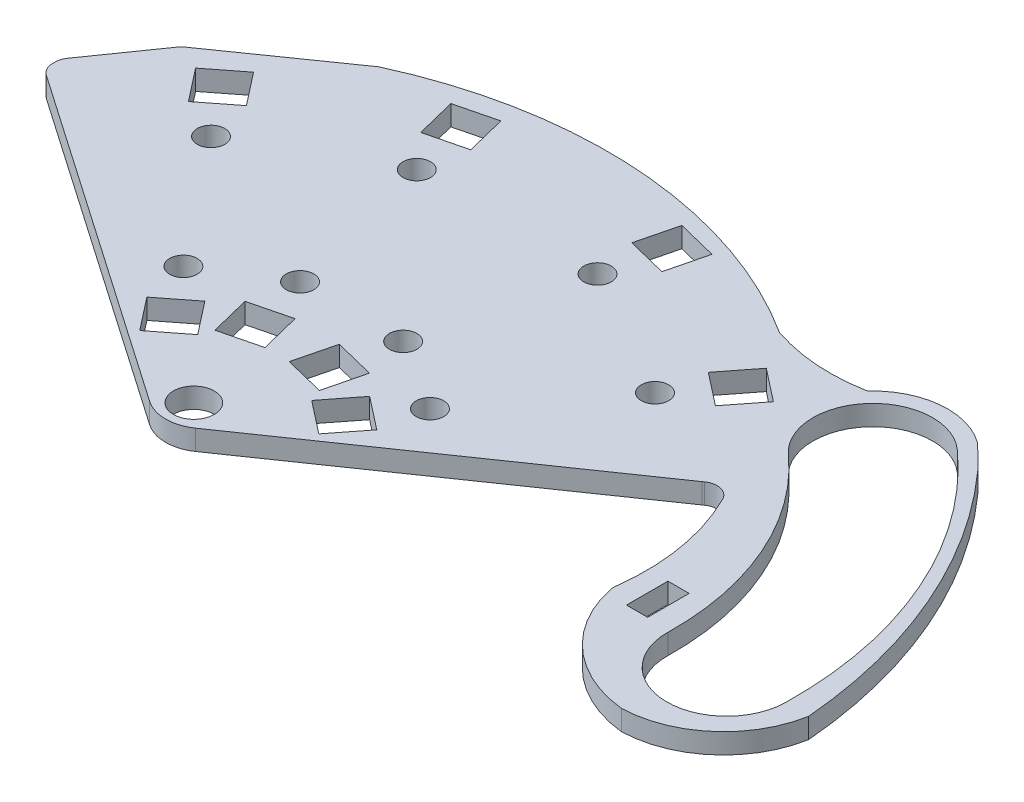
SolidWorks part; units mm, degrees
ref_plane "Front Plane" through (0, 0, 0) normal (0, 0, 1) x (1, 0, 0)
ref_plane "Top Plane" through (0, 0, 0) normal (0, 1, 0) x (1, 0, 0)
ref_plane "Right Plane" through (0, 0, 0) normal (1, 0, 0) x (0, 0, -1)
sketch "Sketch1" plane through (0, 0, 0) normal (0, 1, 0) x (1, 0, 0)
  line L0 (0, 0) -> (0, 16.5491) construction
  line L1 (46.4032, 26.2532) -> (50.582, 29.1399)
  line L2 (-57.15, 35.4293) -> (-57.15, 35.0096)
  line L3 (-48.9805, 47.6303) -> (-31.1233, 60.1341)
  line L4 (-46.4032, 26.2532) -> (-50.582, 29.1399)
  line L5 (-14.1946, 62.3609) -> (-20.4792, 60.794)
  line L6 (-3.4719, 19.3545) -> (-9.7565, 17.7876)
  line L7 (-3.4719, 19.3545) -> (-1.905, 13.0699)
  line L8 (-1.905, 13.0699) -> (-8.1896, 11.503)
  line L9 (-9.7565, 17.7876) -> (-8.1896, 11.503)
  line L10 (-12.6277, 56.0763) -> (-18.9123, 54.5094)
  line L11 (-20.4792, 60.794) -> (-18.9123, 54.5094)
  line L12 (-14.1946, 62.3609) -> (-12.6277, 56.0763)
  line L13 (-12.927, 14.6546) -> (-18.031, 10.667)
  line L14 (-36.2273, 44.4777) -> (-41.3313, 40.49)
  line L15 (-8.9394, 9.5507) -> (-14.0433, 5.563)
  line L16 (-40.215, 49.5816) -> (-36.2273, 44.4777)
  line L17 (-18.031, 10.667) -> (-14.0433, 5.563)
  line L18 (-45.3189, 45.594) -> (-41.3313, 40.49)
  line L19 (-12.927, 14.6546) -> (-8.9394, 9.5507)
  line L20 (-40.215, 49.5816) -> (-45.3189, 45.594)
  line L22 (40.215, 49.5816) -> (45.3189, 45.594)
  line L23 (45.3189, 45.594) -> (41.3313, 40.49)
  line L24 (40.215, 49.5816) -> (36.2273, 44.4777)
  line L25 (36.2273, 44.4777) -> (41.3313, 40.49)
  line L26 (8.9394, 9.5507) -> (14.0433, 5.563)
  line L27 (18.031, 10.667) -> (14.0433, 5.563)
  line L28 (12.927, 14.6546) -> (18.031, 10.667)
  line L29 (12.927, 14.6546) -> (8.9394, 9.5507)
  line L30 (9.7565, 17.7876) -> (8.1896, 11.503)
  line L31 (1.905, 13.0699) -> (8.1896, 11.503)
  line L32 (3.4719, 19.3545) -> (1.905, 13.0699)
  line L33 (3.4719, 19.3545) -> (9.7565, 17.7876)
  line L34 (14.1946, 62.3609) -> (12.6277, 56.0763)
  line L35 (20.4792, 60.794) -> (18.9123, 54.5094)
  line L36 (12.6277, 56.0763) -> (18.9123, 54.5094)
  line L37 (14.1946, 62.3609) -> (20.4792, 60.794)
  line L38 (-15.77, 55.2929) -> (-6.6142, 18.571) construction
  line L39 (-11.1921, 36.9319) -> (-6.6142, 38.0733) construction
  line L40 (-15.479, 12.6608) -> (-38.7793, 42.4839) construction
  line L41 (-27.1292, 27.5723) -> (-22.7995, 30.9551) construction
  line L42 (15.479, 12.6608) -> (38.7793, 42.4839) construction
  line L43 (15.77, 55.2929) -> (6.6142, 18.571) construction
  line L54 (-56.6906, 36.8862) -> (-49.6043, 47.0066)
  line L55 (0, -5.8023) -> (-46.4032, 26.2532)
  line L56 (0, -5.8023) -> (46.4032, 26.2532)
  line L83 (-50.582, 29.1399) -> (-56.0537, 32.9198)
  line L126 (50.582, 29.1399) -> (50.8104, 29.2968)
  line L141 (64.7524, 12.943) -> (61.425, 12.943)
  line L142 (61.425, 12.943) -> (61.425, 6.4406)
  line L143 (64.7524, 6.4406) -> (61.425, 6.4406)
  line L144 (64.7524, 12.943) -> (64.7524, 6.4406)
  arc A0 (-56.6906, 36.8862) -> (-57.15, 35.4293) centre (-54.61, 35.4293) ccw
  circle A1 centre (0, 0) radius 3.2004
  arc A2 (50.8104, 29.2968) -> (54.5732, 28.3832) centre (52.3039, 27.2423) cw
  arc A3 (-57.15, 35.0096) -> (-56.0537, 32.9198) centre (-54.61, 35.0096) ccw
  circle A5 centre (-14.1722, 49.1468) radius 2.159
  circle A6 centre (-8.0888, 24.7478) radius 2.159
  circle A7 centre (-34.8198, 37.5191) radius 2.159
  circle A8 centre (-19.3384, 17.7038) radius 2.159
  arc A9 (-30.3238, 60.5069) -> (-31.1233, 60.1341) centre (-29.6664, 58.0535) ccw
  arc A10 (-49.6043, 47.0066) -> (-48.9805, 47.6303) centre (-47.5236, 45.5497) cw
  circle A11 centre (34.8198, 37.5191) radius 2.159
  arc A12 (54.5732, 28.3832) -> (58.0211, 8.1406) centre (23.2433, 12.632) cw
  arc A13 (58.0211, 8.1406) -> (58.1108, 6.7735) centre (63.0887, 7.7868) ccw
  circle A14 centre (19.3384, 17.7038) radius 2.159
  circle A15 centre (8.0888, 24.7478) radius 2.159
  circle A16 centre (14.1722, 49.1468) radius 2.159
  arc A19 (58.1108, 6.7735) -> (90.5058, 12.8668) centre (74.5492, 8.5391) ccw
  arc A20 (-30.3238, 60.5069) -> (90.5058, 12.8668) centre (15.581, -0.1147) cw
  point P4 (-57.15, 36.2302)
  point P73 (57.15, 36.2302)
  point P76 (49.3474, 47.3734)
  point P79 (30.7564, 60.391)
  point P82 (14.4138, 64.77)
  point P85 (-14.4138, 64.77)
  point P88 (-30.7564, 60.391)
  point P91 (-49.3474, 47.3734)
  point P101 (69.7515, 32.746)
  dimension "D9" = 6.4008
  dimension "D17" = 3.175
  dimension "D18" = 6.35
  dimension "D16" = 4.318
  dimension "D5" = 2.54
  dimension "D2" = 2.54
  dimension "D7" = 2.54
  dimension "D13" = 4.318
  dimension "D3" = 6.477
  dimension "D4" = 6.477
  dimension "D6" = 50.8
  dimension "D8" = 13.208
  dimension "D10" = 6.477
  dimension "D11" = 6.477
  dimension "D12" = 1.905
  dimension "D14" = 3.175
  dimension "D15" = 6.35
extrude "Boss-Extrude1" add sketch "Sketch1" along normal blind 3.175
fillet "Fillet1" radius 6.35 1 edges at (0, 1.5875, 5.8023)
sketch "Sketch2" plane through (0, 3.175, 0) normal (0, 1, 0) x (1, 0, 0)
  arc A0 (77.7534, 5.8298) -> (59.9744, 46.5311) centre (24.5155, 6.8082) ccw construction
  arc A1 (87.1352, 5.6574) -> (66.2231, 53.5312) centre (24.5155, 6.8082) ccw
  arc A2 (68.3717, 6.0022) -> (53.7257, 39.531) centre (24.5155, 6.8082) ccw
  arc A3 (68.3717, 6.0022) -> (87.1352, 5.6574) centre (77.7534, 5.8298) ccw
  arc A4 (66.2231, 53.5312) -> (53.7257, 39.531) centre (59.9744, 46.5311) ccw
  point P3 (73.3103, 28.1227)
extrude "Cut-Extrude1" cut sketch "Sketch2" against normal through all
sketch "Sketch3" plane through (0, 3.175, 0) normal (0, 1, 0) x (1, 0, 0)
  arc A1 (91.0822, -2.1838) -> (68.379, 54.7509) centre (11.4199, -0.956) ccw
  arc A3 (91.0822, -2.1838) -> (58.0196, 7.454) centre (77.1026, 11.3886) cw
  arc A4 (58.0211, 8.1406) -> (58.1108, 6.7735) centre (63.0887, 7.7868) ccw construction
  arc A5 (68.379, 54.7509) -> (51.2622, 54.4242) centre (59.9744, 46.5311) ccw
  arc A6 (36.3835, 55.4751) -> (-31.1233, 60.1341) centre (-1.632, -3.9523) ccw
  arc A7 (51.2622, 54.4242) -> (36.3835, 55.4751) centre (45.8158, 83.1639) cw
  arc A8 (-31.1233, 60.1341) -> (123.016, -2.1838) centre (29.4717, -11.7739) cw
  arc A9 (123.016, -2.1838) -> (58.0196, 7.454) centre (91.4101, 8.6524) cw
extrude "Cut-Extrude2" cut sketch "Sketch3" against normal through all
